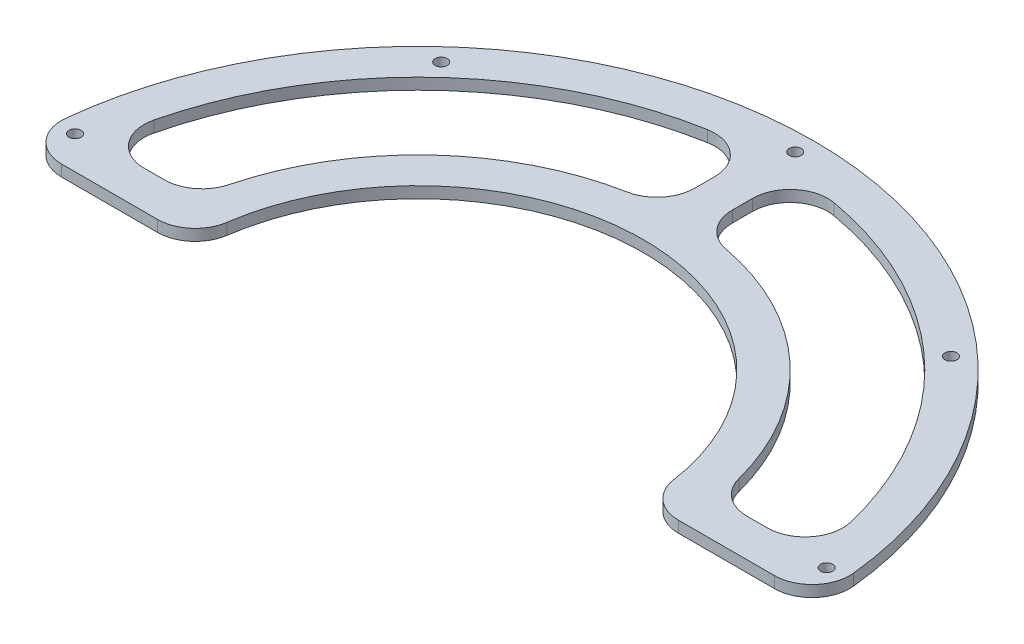
SolidWorks part; units mm, degrees
ref_plane "前视基准面" through (0, 0, 0) normal (0, 0, 1) x (1, 0, 0)
ref_plane "上视基准面" through (0, 0, 0) normal (0, 1, 0) x (1, 0, 0)
ref_plane "右视基准面" through (0, 0, 0) normal (1, 0, 0) x (0, 0, -1)
other "Configuration Table"
sketch "草图2" plane through (0, 0, 0) normal (0, 1, 0) x (1, 0, 0)
  line L0 (-94.4722, 0) -> (-69.0496, 0)
  line L1 (94.4722, 0) -> (69.0496, 0)
  line L25 (0, 0) -> (0, 52.5)
  line L33 (-82.6136, 10) -> (-77.2221, 10)
  line L35 (77.2221, 10) -> (82.6136, 10)
  line L37 (-5, 78.347) -> (-5, 83.666)
  line L38 (5, 78.347) -> (5, 83.666)
  line L44 (0, 0) -> (0, 100) construction
  line L45 (0, 0) -> (67.559, 73.7277) construction
  line L46 (0, 0) -> (0, 100) construction
  line L47 (0, 0) -> (-67.559, 73.7277) construction
  arc A0 (92.3328, 22.3529) -> (16.7647, 93.5091) centre (0, 0) ccw
  arc A1 (104.4167, 11.0526) -> (-104.4167, 11.0526) centre (0, 0) ccw
  arc A2 (67.5415, 17.4928) -> (13.1196, 68.5254) centre (0, 0) ccw
  arc A24 (-16.7647, 93.5091) -> (-92.3328, 22.3529) centre (0, 0) ccw
  arc A25 (-13.1196, 68.5254) -> (-67.5415, 17.4928) centre (0, 0) ccw
  arc A29 (-82.6136, 10) -> (-92.3328, 22.3529) centre (-82.6136, 20) cw
  arc A30 (-77.2221, 10) -> (-67.5415, 17.4928) centre (-77.2221, 20) ccw
  arc A31 (77.2221, 10) -> (67.5415, 17.4928) centre (77.2221, 20) cw
  arc A32 (13.1196, 68.5254) -> (5, 78.347) centre (15, 78.347) cw
  arc A33 (-5, 78.347) -> (-13.1196, 68.5254) centre (-15, 78.347) cw
  arc A40 (82.6136, 10) -> (92.3328, 22.3529) centre (82.6136, 20) ccw
  arc A41 (16.7647, 93.5091) -> (5, 83.666) centre (15, 83.666) ccw
  arc A42 (-5, 83.666) -> (-16.7647, 93.5091) centre (-15, 83.666) ccw
  arc A47 (104.4167, 11.0526) -> (94.4722, 0) centre (94.4722, 10) cw
  arc A48 (-94.4722, 0) -> (-104.4167, 11.0526) centre (-94.4722, 10) cw
  circle A49 centre (0, 0) radius 100 construction
  circle A50 centre (0, 100) radius 1.6
  circle A51 centre (67.559, 73.7277) radius 1.6
  circle A52 centre (99.6195, 8.7156) radius 1.6
  circle A53 centre (-67.559, 73.7277) radius 1.6
  circle A54 centre (-99.6195, 8.7156) radius 1.6
  arc A55 (59.1529, 8.5667) -> (-59.1529, 8.5667) centre (0, 0) ccw
  arc A56 (59.1529, 8.5667) -> (69.0496, 0) centre (69.0496, 10) ccw
  arc A57 (-59.1529, 8.5667) -> (-69.0496, 0) centre (-69.0496, 10) cw
  point P7 (59.77, 0)
  point P10 (-59.77, 0)
  point P73 (0, 52.5)
  point P98 (69.0496, 10)
  point P101 (5, 69.5906)
  point P104 (-5, 69.5906)
  point P128 (-58.9275, 10)
  point P136 (105, 0)
  dimension "D1" = 190
  dimension "D2" = 210
  dimension "D3" = 139.54
  dimension "D4" = 10
  dimension "D11" = 10
  dimension "D15" = 10
  dimension "D16" = 200
  dimension "D17" = 3.2
  dimension "D18" = 3
  dimension "D20" = 3
extrude "凸台-拉伸1" add sketch "草图2" along normal blind 3
